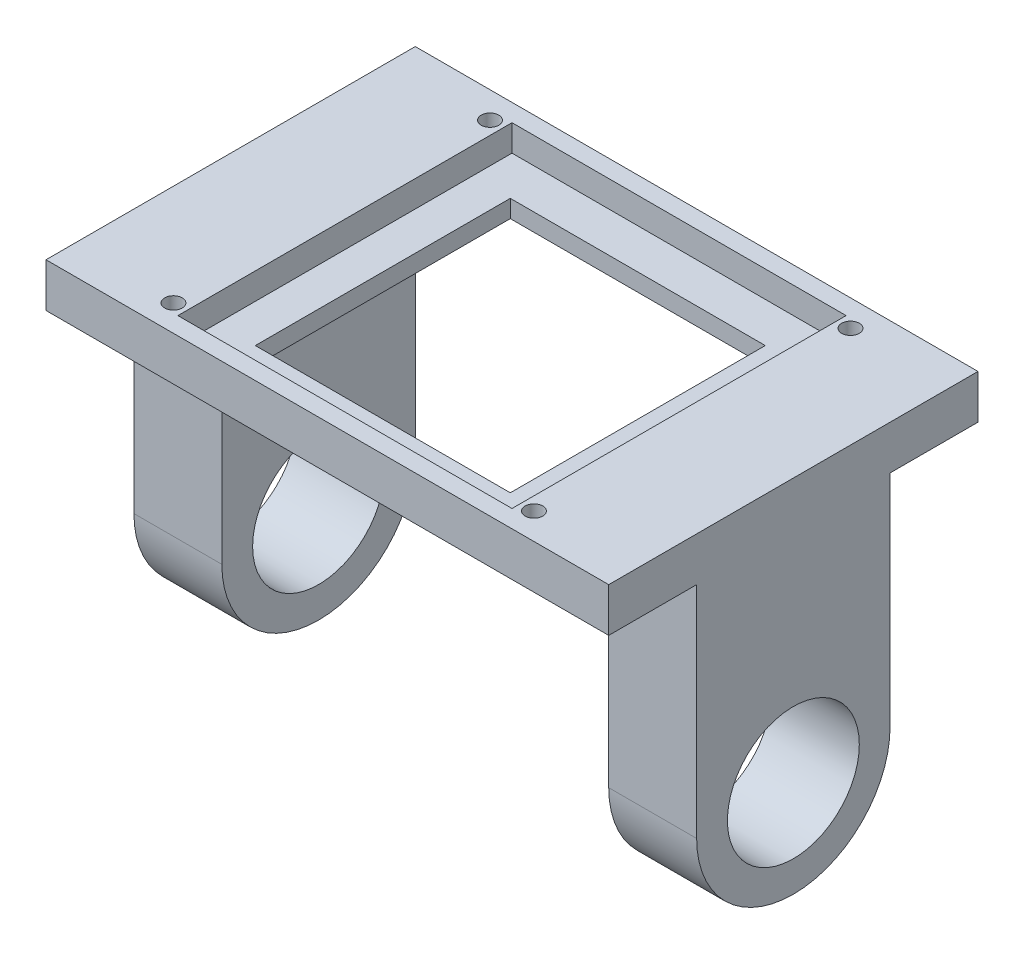
SolidWorks part; units mm, degrees
ref_plane "Front Plane" through (0, 0, 0) normal (0, 0, 1) x (1, 0, 0)
ref_plane "Top Plane" through (0, 0, 0) normal (0, 1, 0) x (1, 0, 0)
ref_plane "Right Plane" through (0, 0, 0) normal (1, 0, 0) x (0, 0, -1)
sketch "Sketch1" plane through (0, 0, 0) normal (1, 0, 0) x (0, 0, -1)
  circle A0 centre (0, 0) radius 7.5
  circle A1 centre (0, 0) radius 11
extrude "Extrude-Thin1" add sketch "Sketch1" along normal blind 10 thin contours A0
sketch "Sketch3" plane through (0, 0, 0) normal (1, 0, 0) x (0, 0, -1)
  line L1 (-11, 0) -> (-11, 30)
  line L2 (11, 0) -> (11, 30)
  line L3 (-11, 30) -> (11, 30)
  arc A1 (11, 0) -> (-11, 0) centre (0, 0) ccw
  point P1 (0, 0)
extrude "Boss-Extrude2" add sketch "Sketch3" along normal blind 10
sketch "Sketch6" plane through (0, 0, 11) normal (0, 0, 1) x (1, 0, 0)
  line L0 (10, 30) -> (10, 0) construction
  line L1 (0, 30) -> (10, 30)
  line L2 (0, 30) -> (0, 25)
  line L3 (0, 25) -> (10, 25)
  line L4 (10, 30) -> (10, 25)
extrude "Boss-Extrude3" add sketch "Sketch6" along normal blind 10
sketch "Sketch8" plane through (0, 0, -11) normal (0, 0, -1) x (-1, 0, 0)
  line L0 (0, 0) -> (0, 30) construction
  line L1 (-10, 30) -> (0, 30)
  line L2 (-10, 30) -> (-10, 25)
  line L3 (-10, 25) -> (0, 25)
  line L4 (0, 30) -> (0, 25)
extrude "Boss-Extrude4" add sketch "Sketch8" along normal blind 10
sketch "Sketch9" plane through (0, 0, 0) normal (-1, 0, 0) x (0, 0, 1)
  line L1 (-21, 30) -> (21, 30)
  line L2 (-21, 30) -> (-21, 25)
  line L3 (-21, 25) -> (21, 25)
  line L4 (21, 30) -> (21, 25)
extrude "Boss-Extrude5" add sketch "Sketch9" along normal blind 54
pattern_linear "LPattern3" count 2 spacing 54 along (-1, 0, 0) of "Boss-Extrude2"
sketch "Sketch15" plane through (-54, 0, 0) normal (-1, 0, 0) x (0, 0, 1)
  circle A0 centre (0, 0) radius 11
extrude "Boss-Extrude6" add sketch "Sketch15" against normal blind 10
sketch "Sketch17" plane through (-54, 0, 0) normal (-1, 0, 0) x (0, 0, 1)
  circle A0 centre (0, 0) radius 7.5
extrude "Cut-Extrude1" cut sketch "Sketch17" against normal blind 10 contours A0
sketch "Sketch19" plane through (0, 30, 0) normal (0, 1, 0) x (1, 0, 0)
  line L7 (-41, 19) -> (-3, 19)
  line L8 (-41, 19) -> (-41, -19)
  line L9 (-3, 19) -> (-3, -19)
  line L10 (-41, -19) -> (-3, -19)
  line L11 (-41, 19) -> (-3, -19) construction
  line L12 (-3, 19) -> (-41, -19) construction
extrude "Cut-Extrude3" cut sketch "Sketch19" against normal blind 3
sketch "Sketch25" plane through (0, 27, 0) normal (0, 1, 0) x (1, 0, 0)
  line L5 (-36.645, -14.5492) -> (-7.645, -14.5492)
  line L6 (-36.645, -14.5492) -> (-36.645, 14.4508)
  line L7 (-36.645, 14.4508) -> (-7.645, 14.4508)
  line L8 (-7.645, -14.5492) -> (-7.645, 14.4508)
  line L9 (-36.645, -14.5492) -> (-7.645, 14.4508) construction
  line L10 (-36.645, 14.4508) -> (-7.645, -14.5492) construction
extrude "Cut-Extrude4" cut sketch "Sketch25" against normal blind 2
sketch "Sketch26" plane through (0, 30, 0) normal (0, 1, 0) x (1, 0, 0)
  circle A0 centre (-1.5, 17.9974) radius 1.0026
extrude "Cut-Extrude5" cut sketch "Sketch26" against normal blind 3
pattern_linear "LPattern4" count 2 spacing 36 along (0, 0, 1) count 2 spacing 41 along (-1, 0, 0) of "Cut-Extrude5"
